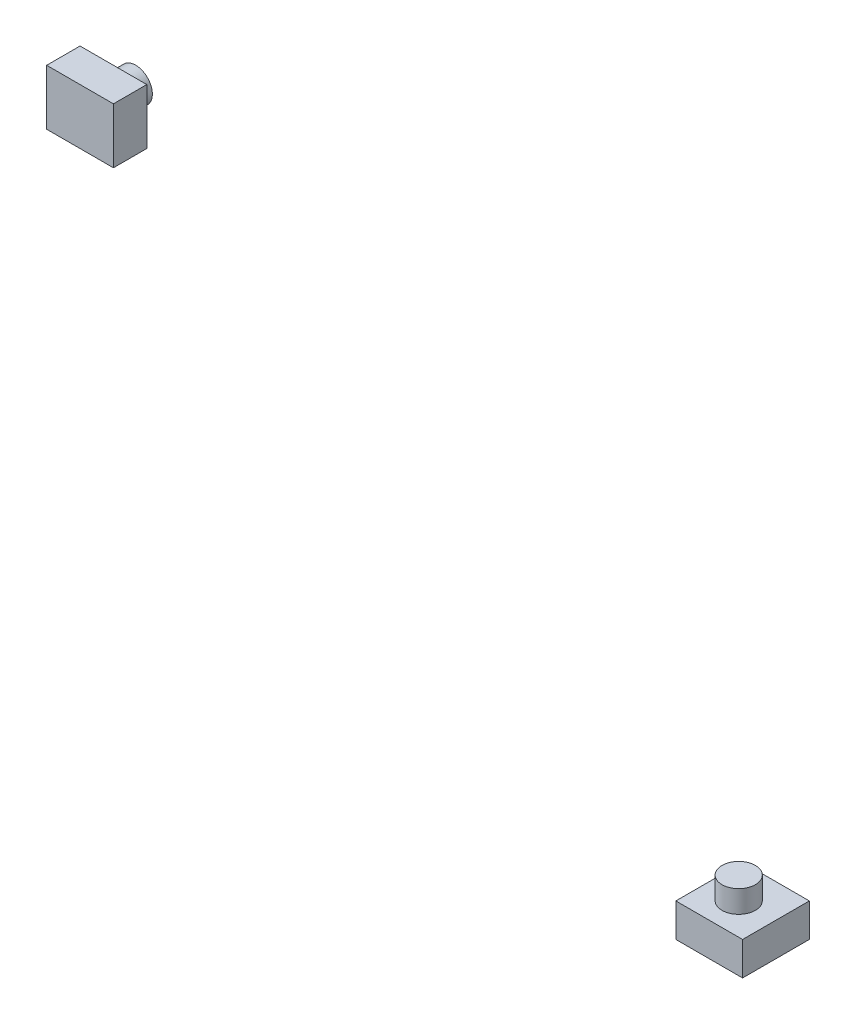
SolidWorks part; units mm, degrees
ref_plane "Front Plane" through (0, 0, 0) normal (0, 0, 1) x (1, 0, 0)
ref_plane "Top Plane" through (0, 0, 0) normal (0, 1, 0) x (1, 0, 0)
ref_plane "Right Plane" through (0, 0, 0) normal (1, 0, 0) x (0, 0, -1)
sketch "Sketch1" plane through (0, 0, 0) normal (0, 1, 0) x (1, 0, 0)
  circle A0 centre (0, 0) radius 9.525
  dimension "D1" = 19.05
extrude "Extrude1" add sketch "Sketch1" against normal blind 12.7
ref_plane "Plane1" through (0, -12.7, 0) normal (0, -1, 0) x (1, 0, 0)
sketch "Sketch2" plane through (0, -12.7, 0) normal (0, -1, 0) x (1, 0, 0)
  line L1 (-17.8582, 18.0318) -> (20.2418, 18.0318)
  line L2 (-17.8582, 18.0318) -> (-17.8582, -20.0682)
  line L3 (-17.8582, -20.0682) -> (20.2418, -20.0682)
  line L4 (20.2418, 18.0318) -> (20.2418, -20.0682)
  point P0 (0, 0)
  dimension "D1" = 38.1
  dimension "D2" = 38.1
extrude "Extrude2" add sketch "Sketch2" along normal blind 19.05
sketch3d "3DSketch2"
  line L3 (0, 0, 0) -> (0, 0, -189.23)
  line L4 (0, 0, -189.23) -> (-533.4, 0, -189.23)
  line L5 (-533.4, 0, -189.23) -> (-533.4, 29.464, -189.23)
  line L6 (-533.4, 0, -189.23) -> (-533.4, 29.464, -189.23)
  dimension "D3" = 189.23
  dimension "D4" = 533.4
  dimension "D5" = 29.464
ref_plane "Plane2" through (0, 0, -189.23) normal (0, 0, 1) x (1, 0, 0)
sketch "Sketch3" plane through (0, 0, -189.23) normal (0, 0, 1) x (1, 0, 0)
  circle A0 centre (-533.4, 29.464) radius 9.525
  dimension "D1" = 19.05
extrude "Extrude3" add sketch "Sketch3" along normal blind 12.7
ref_plane "Plane3" through (0, 0, -176.53) normal (0, 0, 1) x (1, 0, 0)
sketch "Sketch4" plane through (0, 0, -176.53) normal (0, 0, 1) x (1, 0, 0)
  line L1 (-552.45, 45.2814) -> (-514.35, 45.2814)
  line L2 (-552.45, 45.2814) -> (-552.45, 13.6466)
  line L3 (-552.45, 13.6466) -> (-514.35, 13.6466)
  line L4 (-514.35, 45.2814) -> (-514.35, 13.6466)
  line L5 (-552.45, 45.2814) -> (-514.35, 13.6466) construction
  line L6 (-552.45, 13.6466) -> (-514.35, 45.2814) construction
  point P0 (-533.4, 29.464)
  dimension "D1" = 38.1
extrude "Extrude4" add sketch "Sketch4" along normal blind 19.05
